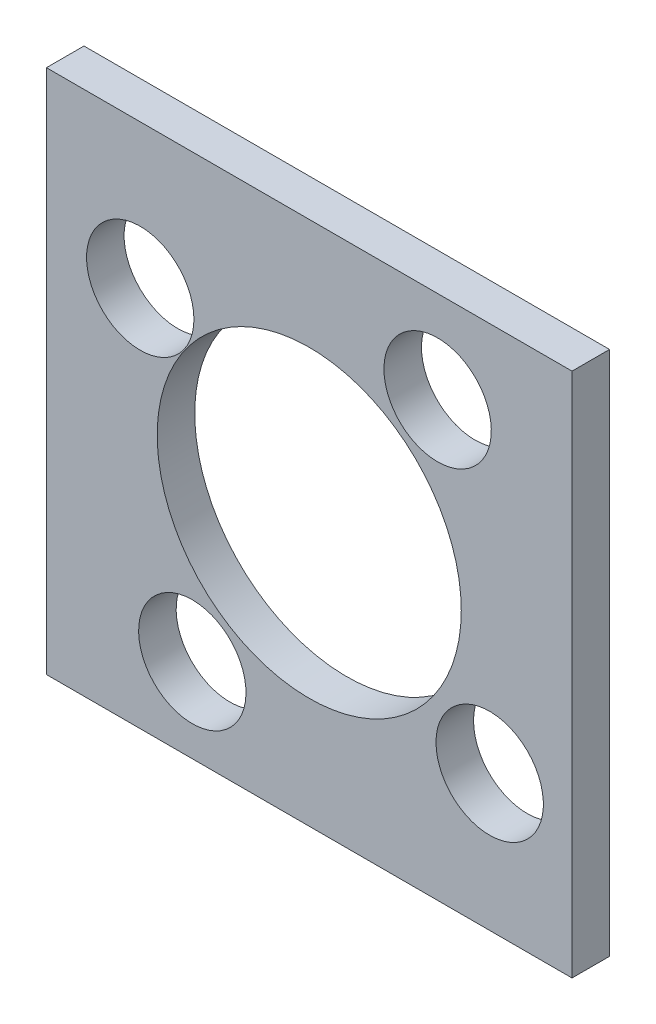
SolidWorks part; units mm, degrees
ref_plane "Front Plane" through (0, 0, 0) normal (0, 0, 1) x (1, 0, 0)
ref_plane "Top Plane" through (0, 0, 0) normal (0, 1, 0) x (1, 0, 0)
ref_plane "Right Plane" through (0, 0, 0) normal (1, 0, 0) x (0, 0, -1)
sketch "Sketch1" plane through (0, 0, 0) normal (0, 0, 1) x (1, 0, 0)
  line L1 (-70, 70) -> (70, 70)
  line L2 (-70, 70) -> (-70, -70)
  line L3 (-70, -70) -> (70, -70)
  line L4 (70, 70) -> (70, -70)
  line L5 (-70, 70) -> (70, -70) construction
  line L6 (-70, -70) -> (70, 70) construction
  point P0 (0, 0)
  dimension "D1" = 140
  dimension "D2" = 140
extrude "Boss-Extrude1" add sketch "Sketch1" along normal blind 10
sketch "Sketch2" plane through (0, 0, 10) normal (0, 0, 1) x (1, 0, 0)
  circle A0 centre (-45.016, 31.5999) radius 14.3
  dimension "D1" = 55
extrude "Cut-Extrude4" cut sketch "Sketch2" against normal through all
pattern_circular "CirPattern4" count 4 over 360 about axis through (1.5255, -1.0708, 0) along (0, 0, 1) of "Cut-Extrude4"
sketch "Sketch4" plane through (0, 0, 10) normal (0, 0, 1) x (1, 0, 0)
  circle A0 centre (0, 0) radius 40.5
extrude "Cut-Extrude5" cut sketch "Sketch4" against normal through all
